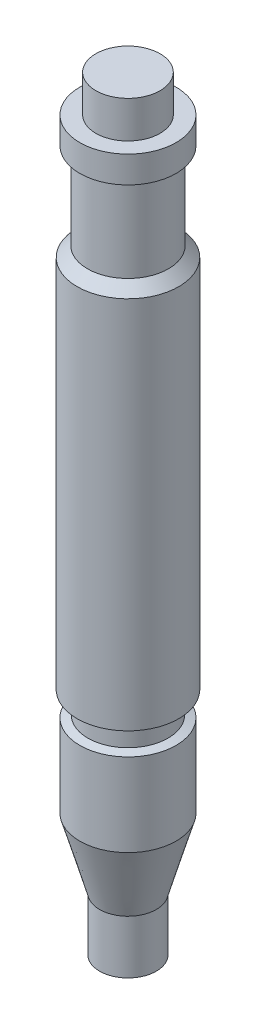
SolidWorks part; units mm, degrees
ref_plane "前视基准面" through (0, 0, 0) normal (0, 0, 1) x (1, 0, 0)
ref_plane "上视基准面" through (0, 0, 0) normal (0, 1, 0) x (1, 0, 0)
ref_plane "右视基准面" through (0, 0, 0) normal (1, 0, 0) x (0, 0, -1)
sketch "草图1" plane through (0, 0, 0) normal (0, 0, 1) x (1, 0, 0)
  line L0 (0, 26.5392) -> (0, -32.5427) construction
  line L1 (0, 81.9239) -> (6, 81.9239)
  line L2 (6, 81.9239) -> (6, 75.0108)
  line L3 (6, 75.0108) -> (9, 75.0108)
  line L4 (9, 75.0108) -> (9, 70.0108)
  line L5 (9, 70.0108) -> (7.5734, 70.0108)
  line L6 (7.5734, 70.0108) -> (7.5734, 53.8505)
  line L7 (7.5734, 53.8505) -> (9.5, 51.9239)
  line L8 (9.5, 51.9239) -> (9.5, -18.0761)
  line L9 (9.5, -18.0761) -> (0, -18.0761)
  line L10 (0, 81.9239) -> (0, -18.0761)
  dimension "D1" = 19
  dimension "D2" = 100
  dimension "D3" = 5
  dimension "D4" = 70
  dimension "D5" = 6
  dimension "D6" = 9
revolve "旋转1" add sketch "草图1" angle 360 about L0
sketch "草图2" plane through (0, 0, 0) normal (0, 0, 1) x (1, 0, 0)
  line L0 (0, -18.0761) -> (0, -53.8778) construction
  line L1 (-9.5, -18.0761) -> (9.5, -18.0761) construction
  line L2 (7.5, -18.0761) -> (7.5, -22.2201)
  line L3 (7.5, -22.2201) -> (9, -22.649)
  line L4 (9, -22.649) -> (9, -38.1551)
  line L5 (9, -38.1551) -> (5.3052, -51.0761)
  line L6 (5.3052, -51.0761) -> (5.3052, -61.0761)
  line L7 (5.3052, -61.0761) -> (3, -61.0761)
  line L8 (3, -61.0761) -> (3, -40.6707)
  line L9 (3, -40.6707) -> (0, -40.6707)
  line L10 (0, -18.0761) -> (7.5, -18.0761)
  line L11 (6, 81.9239) -> (-6, 81.9239) construction
  line L12 (0, -18.0761) -> (0, -40.6707)
  dimension "D1" = 6
  dimension "D2" = 18
  dimension "D3" = 143
  dimension "D4" = 10
  dimension "D5" = 15
revolve "旋转2" add sketch "草图2" angle 360 about L0
